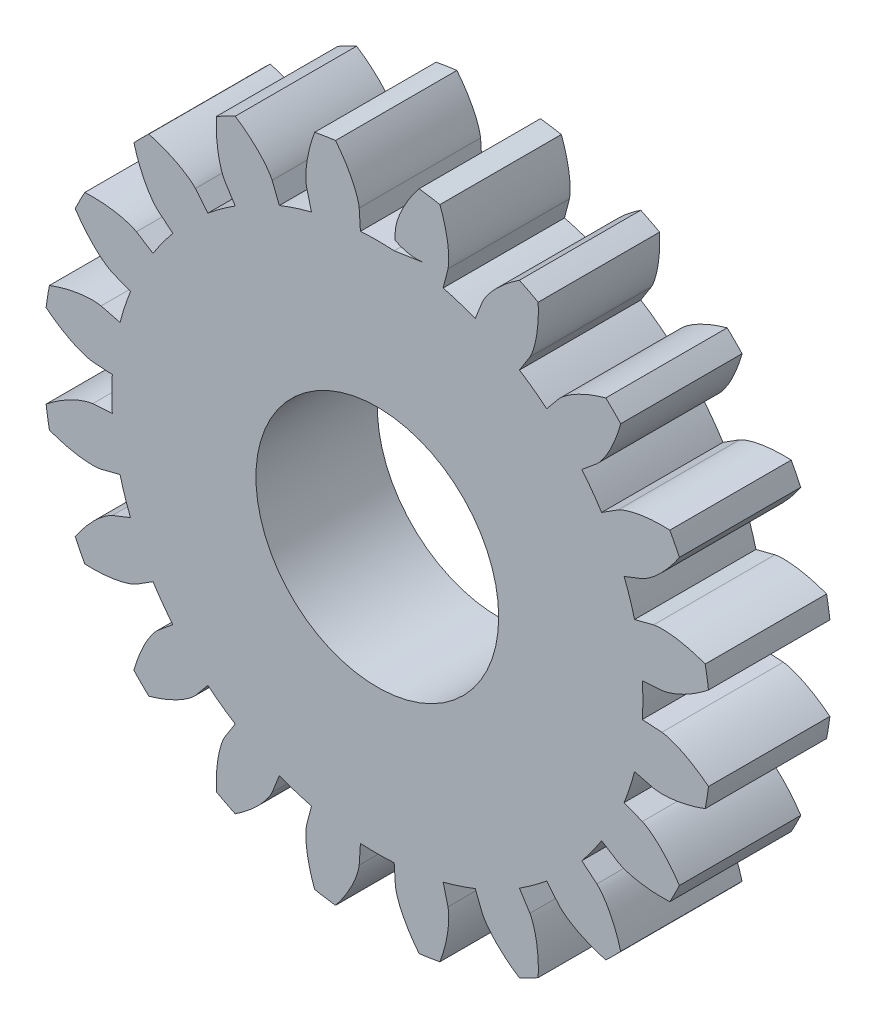
SolidWorks part; units mm, degrees
ref_plane "Front Plane" through (0, 0, 0) normal (0, 0, 1) x (1, 0, 0)
ref_plane "Top Plane" through (0, 0, 0) normal (0, 1, 0) x (1, 0, 0)
ref_plane "Right Plane" through (0, 0, 0) normal (1, 0, 0) x (0, 0, -1)
sketch "Sketch1" plane through (0, 0, 0) normal (0, 0, 1) x (1, 0, 0)
  circle A0 centre (0, 0) radius 27.5
  dimension "GearOverall" = 55
extrude "Boss-Extrude1" add sketch "Sketch1" along normal mid plane 10
sketch "Sketch2" plane through (0, 0, 5) normal (0, 0, 1) x (1, 0, 0)
  line L0 (0, 0) -> (0, 27.5) construction
  line L1 (0, 0) -> (-27.5, 0) construction
  line L2 (-1.4922, 23.4426) -> (0, 0) construction
  line L3 (0, 0) -> (-3.9344, 23.1582) construction
  line L4 (-3.9344, 23.1582) -> (-1.5092, 23.5702) construction
  line L5 (0, 0) -> (-6.3336, 22.62) construction
  line L6 (-6.3336, 22.62) -> (-1.5958, 23.9466) construction
  line L7 (0, 0) -> (-8.6633, 21.8341) construction
  line L8 (-8.6633, 21.8341) -> (-1.8036, 24.5559) construction
  line L9 (0, 0) -> (-10.8981, 20.8089) construction
  line L10 (-10.8981, 20.8089) -> (-2.1812, 25.3742) construction
  line L11 (0, 0) -> (-13.0136, 19.5558) construction
  line L12 (-13.0136, 19.5558) -> (-2.7736, 26.37) construction
  line L13 (0, 0) -> (-14.9864, 18.0883) construction
  line L14 (-14.9864, 18.0883) -> (-3.6205, 27.5051) construction
  line L15 (0, 0) -> (-16.795, 16.4227) construction
  line L16 (-16.795, 16.4227) -> (-4.7559, 28.7348) construction
  circle A0 centre (0, 0) radius 27.5 construction
  circle A1 centre (0, 0) radius 23.49 construction
  circle A2 centre (0, 0) radius 25 construction
  arc A3 (0, 23.49) -> (-1.4922, 23.4426) centre (0, 0) ccw construction
  arc A4 (-1.4922, 23.4426) -> (1.4922, 23.4426) centre (0, 0) cw
  arc A5 (-4.7559, 28.7348) -> (4.7559, 28.7348) centre (0, 1.6492) cw
  spline S0 degree 3 poles (-1.4922, 23.4426) (-1.5097, 23.6135) (-1.5981, 23.9909) (-1.823, 24.6405) (-2.2058, 25.4584) (-3.0904, 26.9331) (-4.0211, 28.0142) (-4.7559, 28.7348) knots 0 0 0 0 0.081636 0.183677 0.326533 0.510206 1 1 1 1
  spline S1 degree 3 poles (1.4922, 23.4426) (1.5097, 23.6135) (1.5981, 23.9909) (1.823, 24.6405) (2.2058, 25.4584) (3.0904, 26.9331) (4.0211, 28.0142) (4.7559, 28.7348) knots 0 0 0 0 0.081636 0.183677 0.326533 0.510206 1 1 1 1
  point P14 (-1.96, 24.923)
  dimension "BaseCircle" = 46.98
  dimension "PCD" = 50
  dimension "MirrorDist" = 1.96
  dimension "D2" = 6
  dimension "InvoluteGAP" = 2.46
  dimension "D3" = 4.92
  dimension "D4" = 6
  dimension "D5" = 7.38
  dimension "D6" = 6
  dimension "D7" = 9.84
  dimension "D8" = 6
  dimension "D9" = 12.3
  dimension "D10" = 6
  dimension "D11" = 14.76
  dimension "D12" = 6
  dimension "D13" = 17.22
  dimension "D14" = 6
extrude "Cut-Extrude1" cut sketch "Sketch2" against normal through all contours A5 S1 A4 S0
sketch "Sketch4" plane through (0, 0, 5) normal (0, 0, 1) x (1, 0, 0)
  line L0 (0, 0) -> (-1.4922, 23.4426)
  line L1 (0, 0) -> (1.4922, 23.4426)
  arc A0 (1.4922, 23.4426) -> (-1.4922, 23.4426) centre (0, 0) ccw construction
  arc A1 (1.4922, 23.4426) -> (-1.4922, 23.4426) centre (0, 0) ccw
  circle A2 centre (0, 0) radius 21.875
  arc M1 (1.4922, 23.4426) -> (-1.4922, 23.4426) centre (0, 0) ccw
  dimension "Dedendum" = 43.75
extrude "Cut-Extrude2" cut sketch "Sketch4" against normal through all contours A2 L1 L0 M1
pattern_circular "CirPattern1" count 20 over 360 about axis through (0, 0, 5) along (0, 0, -1) of "Cut-Extrude1", "Cut-Extrude2"
sketch "Sketch5" plane through (0, 0, 5) normal (0, 0, 1) x (1, 0, 0)
  circle A0 centre (0, 0) radius 10
  dimension "ID" = 20
extrude "Cut-Extrude3" cut sketch "Sketch5" against normal through all
sketch "Sketch6" plane through (0, 0, 5) normal (0, 0, 1) x (1, 0, 0)
  line L0 (1.3896, 21.8308) -> (1.4922, 23.4426) construction
  line L1 (1.4409, 22.6367) -> (1.3896, 21.8308)
  spline S0 degree 2 poles (1.3896, 21.8308) (2.5542, 22.0058) (3.7172, 22.1908) knots 0 0 0 1 1 1
  spline S1 degree 2 poles (3.7172, 22.1908) (2.5416, 22.0616) (1.4409, 22.6367) knots 0 0 0 1 1 1
  dimension "TeethTail" = 22.5
  dimension "D2" = 22
  dimension "D3" = 22.4
  dimension "TeethDist2" = 0.5
  dimension "TeethDist1" = 0.5
  dimension "TeethDepth" = 2.3
extrude "Cut-Extrude4" cut sketch "Sketch6" against normal through all contours S0 S1 L1
equation "\"D3@Sketch2\"=\"InvoluteGAP@Sketch2\"*2"
equation "\"D5@Sketch2\"=\"InvoluteGAP@Sketch2\"*3"
equation "\"D7@Sketch2\"=\"InvoluteGAP@Sketch2\"*4"
equation "\"D9@Sketch2\"=\"InvoluteGAP@Sketch2\"*5"
equation "\"D11@Sketch2\"=\"InvoluteGAP@Sketch2\"*6"
equation "\"D13@Sketch2\"=\"InvoluteGAP@Sketch2\"*7"
equation "\"D3@Sketch6\"=\"TeethTail@Sketch6\"-0.1"
equation "\"D2@Sketch6\"=\"TeethTail@Sketch6\"-0.5"
